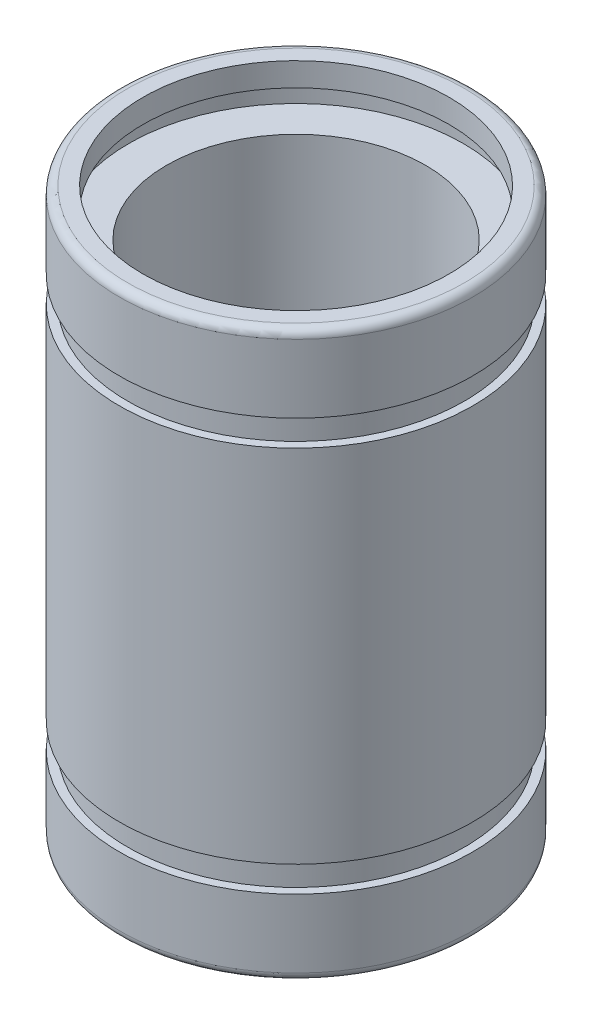
SolidWorks part; units mm, degrees
material "ASTM A36 Steel"
ref_plane "Front" through (0, 0, 0) normal (0, 0, 1) x (1, 0, 0)
ref_plane "Top" through (0, 0, 0) normal (0, 1, 0) x (1, 0, 0)
ref_plane "Right" through (0, 0, 0) normal (1, 0, 0) x (0, 0, -1)
sketch "Sketch1" plane through (0, 0, 0) normal (1, 0, 0) x (0, -1, 0)
  line L0 (12, 7.15) -> (12, 6.5)
  line L1 (12, 6.5) -> (11, 6.5)
  line L2 (11, 6.5) -> (11, 7.1)
  line L3 (11.65, 7.5) -> (8.75, 7.5)
  line L4 (11, 7.1) -> (10, 7.1)
  line L5 (10, 7.1) -> (10, 5.5)
  line L6 (8.75, 7.15) -> (8.75, 7.5)
  line L7 (7.65, 7.5) -> (-7.65, 7.5)
  line L8 (-7.65, 7.5) -> (-7.65, 7.15)
  line L9 (-7.65, 7.15) -> (-8.75, 7.15)
  line L10 (-8.75, 7.15) -> (-8.75, 7.5)
  line L11 (-8.75, 7.5) -> (-11.65, 7.5)
  line L12 (-12, 7.15) -> (-12, 6.5)
  line L13 (-12, 6.5) -> (-11, 6.5)
  line L14 (-11, 6.5) -> (-11, 7.1)
  line L15 (-11, 7.1) -> (-10, 7.1)
  line L16 (-10, 7.1) -> (-10, 5.5)
  line L17 (-10, 5.5) -> (10, 5.5)
  line L18 (10, 5.5) -> (10, 7.1)
  line L19 (7.65, 7.15) -> (8.75, 7.15)
  line L20 (-12, 0) -> (12, 0) construction
  line L21 (0, 5.0091) -> (0, 0) construction
  line L22 (7.65, 7.5) -> (7.65, 7.15)
  arc A0 (11.65, 7.5) -> (12, 7.15) centre (11.65, 7.15) cw
  arc A1 (-11.65, 7.5) -> (-12, 7.15) centre (-11.65, 7.15) ccw
  dimension "D11" = 0.35
  dimension "D1" = 11
  dimension "D2" = 15
  dimension "D3" = 24
  dimension "D4" = 3.25
  dimension "D5" = 1.1
  dimension "D6" = 0.35
  dimension "D7" = 1.6
  dimension "D8" = 1
  dimension "D9" = 13
  dimension "D10" = 1
revolve "Revolve1" add sketch "Sketch1" angle 360 about L20
